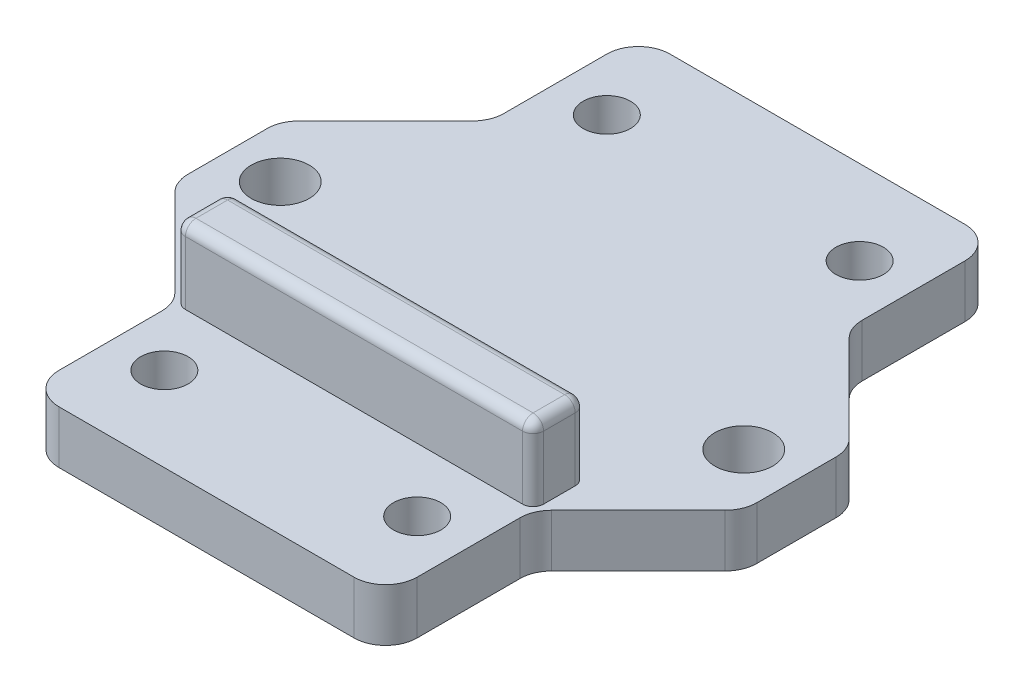
SolidWorks part; units mm, degrees
ref_plane "Front Plane" through (0, 0, 0) normal (0, 0, 1) x (1, 0, 0)
ref_plane "Top Plane" through (0, 0, 0) normal (0, 1, 0) x (1, 0, 0)
ref_plane "Right Plane" through (0, 0, 0) normal (1, 0, 0) x (0, 0, -1)
sketch "Sketch1" plane through (0, 0, 0) normal (0, 1, 0) x (1, 0, 0)
  line L0 (0, 0) -> (0, 57.7309) construction
  line L1 (-17, -29) -> (17, -29)
  line L2 (-17, -29) -> (-17, -15)
  line L3 (-17, 29) -> (17, 29)
  line L4 (17, -29) -> (17, -15)
  line L5 (-17, -29) -> (17, 29) construction
  line L6 (-17, 29) -> (17, -29) construction
  line L7 (-12, -21) -> (12, -21) construction
  line L8 (-12, -21) -> (-12, 21) construction
  line L9 (-12, 21) -> (12, 21) construction
  line L10 (12, -21) -> (12, 21) construction
  line L11 (-12, -21) -> (12, 21) construction
  line L12 (-12, 21) -> (12, -21) construction
  line L13 (0, 0) -> (-36.7434, 0) construction
  line L14 (-17, 15) -> (-27, 5)
  line L15 (-27, 5) -> (-27, -5)
  line L16 (-17, -15) -> (-27, -5)
  line L17 (-17, 15) -> (-17, 29)
  line L18 (17, -15) -> (27, -5)
  line L19 (27, 5) -> (27, -5)
  line L20 (17, 15) -> (27, 5)
  line L21 (17, 15) -> (17, 29)
  circle A0 centre (-12, 21) radius 2.25
  circle A1 centre (12, 21) radius 2.25
  circle A2 centre (-12, -21) radius 2.25
  circle A3 centre (12, -21) radius 2.25
  circle A4 centre (-22, 0) radius 2.75
  circle A5 centre (22, 0) radius 2.75
  point P0 (0, 0)
  point P6 (0, 0)
  point P27 (-27, 0)
  dimension "D1" = 4.5
  dimension "D2" = 4.5
  dimension "D3" = 4.5
  dimension "D4" = 4.5
  dimension "D9" = 5.5
  dimension "D5" = 24
  dimension "D6" = 42
  dimension "D7" = 34
  dimension "D8" = 58
  dimension "D10" = 5
  dimension "D11" = 10
  dimension "D12" = 5
  dimension "D13" = 10
extrude "Boss-Extrude1" add sketch "Sketch1" along normal mid plane 5
fillet "Fillet2" radius 3 12 edges at (17, 0, -15) (27, 0, -5) (17, 0, 15) (27, 0, 5) (17, 0, 29) (-17, 0, 29) (-17, 0, 15) (-27, 0, 5) (-27, 0, -5) (-17, 0, -15) (17, 0, -29) (-17, 0, -29)
sketch "Sketch2" plane through (0, 2.5, 0) normal (0, 1, 0) x (1, 0, 0)
  line L0 (0, 0) -> (-44.4208, 0) construction
  line L1 (-17, -16.2426) -> (-17, -26) construction
  line L2 (-17, -10) -> (17, -10)
  line L3 (-17, -10) -> (-17, -15)
  line L4 (-17, -15) -> (17, -15)
  line L5 (17, -10) -> (17, -15)
  line L6 (17, -26) -> (17, -16.2426) construction
  dimension "D1" = 10
  dimension "D2" = 5
  dimension "D3" = 0
  dimension "D4" = 0
extrude "Boss-Extrude2" add sketch "Sketch2" along normal blind 7
fillet "Fillet3" radius 1 8 edges at (-17, 9.5, 12.5) (17, 9.5, 12.5) (0, 9.5, 15) (0, 9.5, 10) (17, 6, 15) (17, 6, 10) (-17, 6, 15) (-17, 6, 10)
